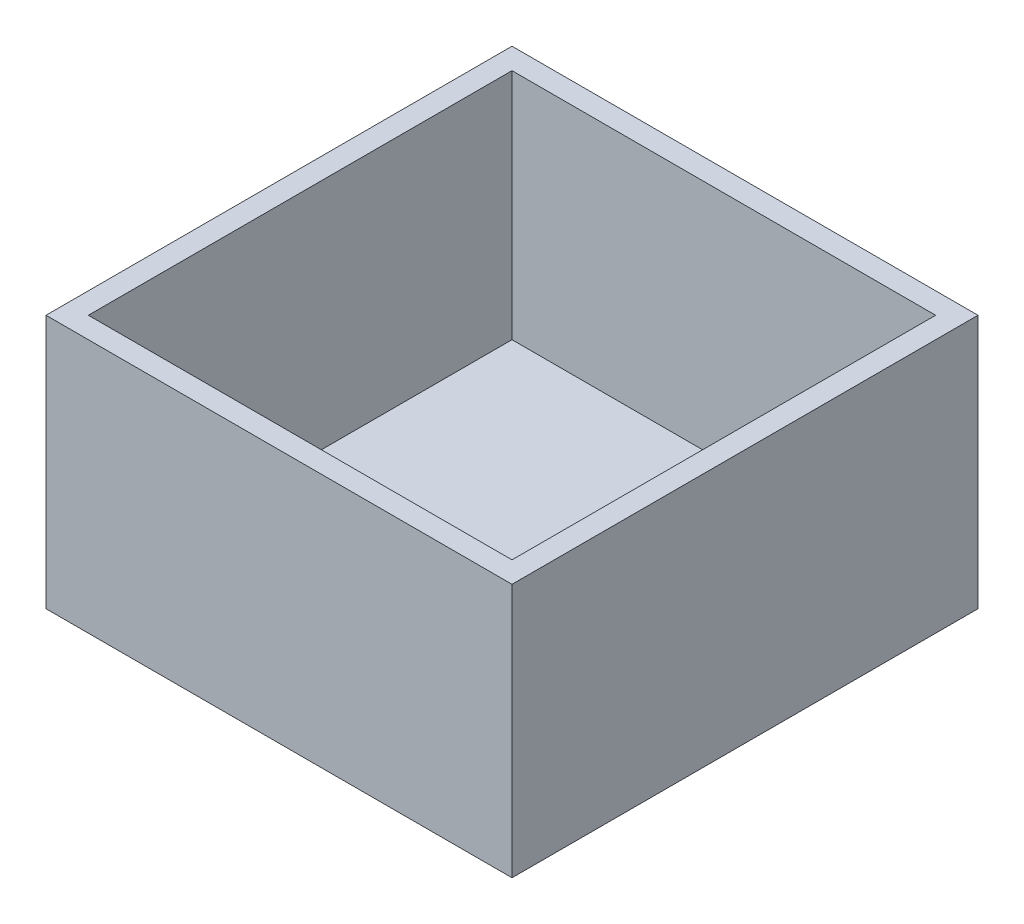
SolidWorks part; units mm, degrees
ref_plane "Front Plane" through (0, 0, 0) normal (0, 0, 1) x (1, 0, 0)
ref_plane "Top Plane" through (0, 0, 0) normal (0, 1, 0) x (1, 0, 0)
ref_plane "Right Plane" through (0, 0, 0) normal (1, 0, 0) x (0, 0, -1)
sketch "Sketch1" plane through (0, 0, 0) normal (0, 1, 0) x (1, 0, 0)
  line L1 (-69.85, -69.85) -> (69.85, -69.85)
  line L2 (-69.85, -69.85) -> (-69.85, 69.85)
  line L3 (-69.85, 69.85) -> (69.85, 69.85)
  line L4 (69.85, -69.85) -> (69.85, 69.85)
  line L5 (-69.85, -69.85) -> (69.85, 69.85) construction
  line L6 (-69.85, 69.85) -> (69.85, -69.85) construction
  point P0 (0, 0)
extrude "Boss-Extrude1" add sketch "Sketch1" along normal blind 76.2
shell "Shell2" thickness 6.35
